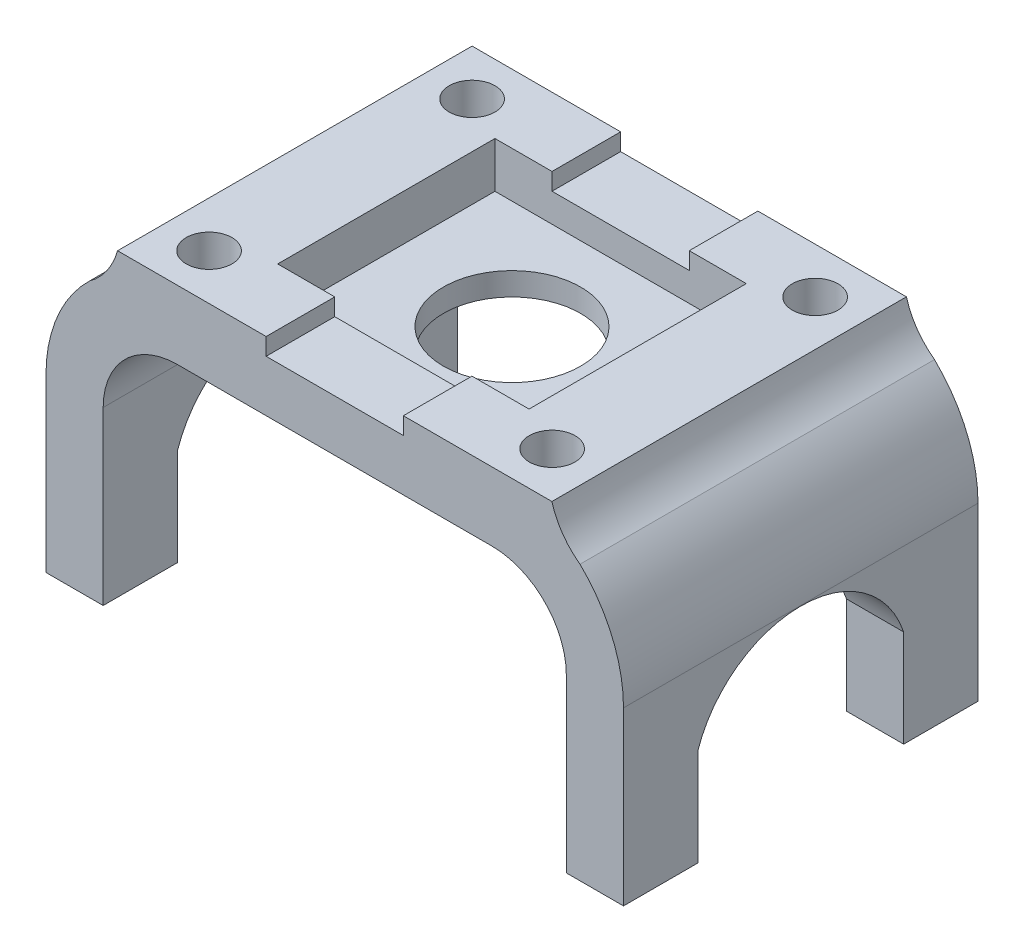
SolidWorks part; units mm, degrees
ref_plane "Piano frontale" through (0, 0, 0) normal (0, 0, 1) x (1, 0, 0)
ref_plane "Piano superiore" through (0, 0, 0) normal (0, 1, 0) x (1, 0, 0)
ref_plane "Piano destro" through (0, 0, 0) normal (1, 0, 0) x (0, 0, -1)
sketch "Schizzo1" plane through (0, 0, 0) normal (0, 0, 1) x (1, 0, 0)
  line L1 (0, 0) -> (-101, 0)
  line L2 (0, 0) -> (0, 55)
  line L3 (0, 55) -> (-101, 55)
  line L4 (-101, 0) -> (-101, 55)
  dimension "D1" = 101
  dimension "D2" = 55
extrude "Estrusione-Estrusione1" add sketch "Schizzo1" against normal blind 62
sketch "Schizzo2" plane through (0, 0, 0) normal (1, 0, 0) x (0, 0, -1)
  line L0 (62, 0) -> (0, 0) construction
  line L1 (13, 0) -> (49, 0)
  line L2 (13, 0) -> (13, 17)
  line L4 (49, 0) -> (49, 17)
  line L5 (0, 0) -> (0, 55) construction
  arc A0 (13, 17) -> (49, 17) centre (31, 10.9172) cw
  dimension "D3" = 19
  dimension "D1" = 13
  dimension "D2" = 36
  dimension "D4" = 17
extrude "Taglio-Estrusione1" cut sketch "Schizzo2" against normal through all
sketch "Schizzo3" plane through (0, 0, 0) normal (0, 0, 1) x (1, 0, 0)
  line L0 (-101, 0) -> (0, 0) construction
  line L1 (-91, 0) -> (-10, 0)
  line L2 (-91, 0) -> (-91, 43) construction
  line L3 (-91, 43) -> (-10, 43) construction
  line L4 (-10, 0) -> (-10, 43) construction
  line L5 (-101, 55) -> (-101, 0) construction
  line L6 (-91, 30) -> (-10, 30) construction
  line L7 (-78, 25.4552) -> (-78, 34.5448) construction
  line L8 (-23, 25.4552) -> (-23, 34.5448) construction
  line L9 (-91, 30) -> (-91, 0)
  line L10 (-78, 43) -> (-23, 43)
  line L11 (-10, 30) -> (-10, 0)
  arc A0 (-91, 30) -> (-78, 43) centre (-78, 30) cw
  arc A1 (-23, 43) -> (-10, 30) centre (-23, 30) cw
  point P13 (-78, 30)
  point P16 (-23, 30)
  dimension "D1" = 81
  dimension "D2" = 10
  dimension "D3" = 43
  dimension "D4" = 30
  dimension "D5" = 13
  dimension "D6" = 13
extrude "Taglio-Estrusione2" cut sketch "Schizzo3" against normal through all
sketch "Schizzo6" plane through (0, 0, 0) normal (0, 0, 1) x (1, 0, 0)
  line L0 (0, 0) -> (0, 55) construction
  line L1 (-10, 0) -> (0, 0) construction
  line L2 (0, 55) -> (-101, 55) construction
  line L3 (0, 55) -> (-12.5, 55) construction
  line L4 (-101, 55) -> (-101, 0) construction
  line L5 (-50.5, 55) -> (-50.5, -49945) construction
  circle A0 centre (-25, 30) radius 25 construction
  circle A1 centre (0, 58.5) radius 13 construction
  point P17 (-50.5, 55)
  dimension "D1" = 25
  dimension "D3" = 101
  dimension "D6" = 50
  dimension "D7" = 26
  dimension "D2" = 30
  dimension "D4" = 3.5
  dimension "D5" = 12.5
sketch "Schizzo7" plane through (0, 0, 0) normal (0, 0, 1) x (1, 0, 0)
  line L0 (0, 55) -> (-101, 55) construction
  line L1 (0, 55) -> (0, 30)
  line L2 (0, 0) -> (0, 55) construction
  line L3 (0, 55) -> (-12.52, 55)
  line L4 (-50.5, 43) -> (-50.5, -49957) construction
  line L5 (-23, 43) -> (-78, 43) construction
  line L7 (-101, 55) -> (-101, 30)
  line L8 (-101, 55) -> (-88.48, 55)
  arc A0 (0, 30) -> (-7.6077, 47.9585) centre (-25, 30) ccw
  circle A1 centre (0, 58.5) radius 13 construction
  arc A2 (-7.6077, 47.9585) -> (-12.52, 55) centre (0, 58.5) cw
  arc A3 (-101, 30) -> (-93.3923, 47.9585) centre (-76, 30) cw
  arc A4 (-93.3923, 47.9585) -> (-88.48, 55) centre (-101, 58.5) ccw
  point P20 (-50.5, 43)
  dimension "D1" = 25
extrude "Taglio-Estrusione4" cut sketch "Schizzo7" against normal through all
sketch "Schizzo8" plane through (0, 55, 0) normal (0, 1, 0) x (1, 0, 0)
  line L0 (-50.5, 62) -> (-50.5, -49938) construction
  line L1 (-12.52, 62) -> (-88.48, 62) construction
  line L2 (-50, 0) -> (0, 0) construction
  line L3 (-62.5, 62) -> (-38.5, 62)
  line L5 (-62.5, 0) -> (-38.5, 0)
  line L6 (-38.5, 62) -> (-38.5, 0)
  line L7 (-62.5, 62) -> (-62.5, 0)
  point P4 (-50.5, 62)
  point P12 (-50.5, 0)
  point P13 (-50.5, 62)
  dimension "D1" = 12
extrude "Taglio-Estrusione5" cut sketch "Schizzo8" against normal blind 3
sketch "Schizzo9" plane through (0, 55, 0) normal (0, 1, 0) x (1, 0, 0)
  line L0 (-12.52, 62) -> (-38.5, 62) construction
  line L1 (-72.48, 50) -> (-28.52, 50)
  line L2 (-72.48, 50) -> (-72.48, 12)
  line L3 (-72.48, 12) -> (-28.52, 12)
  line L4 (-28.52, 50) -> (-28.52, 12)
  line L5 (-50, 0) -> (0, 0) construction
  line L6 (-12.52, 62) -> (-12.52, 0) construction
  line L7 (-88.48, 62) -> (-88.48, 0) construction
  dimension "D1" = 12
  dimension "D2" = 12
  dimension "D3" = 16
  dimension "D4" = 16
extrude "Taglio-Estrusione6" cut sketch "Schizzo9" against normal blind 8
sketch "Schizzo10" plane through (0, 47, 0) normal (0, 1, 0) x (1, 0, 0)
  line L0 (-28.52, 50) -> (-72.48, 12) construction
  circle A0 centre (-50.5, 31) radius 12
  dimension "D1" = 24
extrude "Taglio-Estrusione7" cut sketch "Schizzo10" against normal through all
sketch "Schizzo11" plane through (0, 55, 0) normal (0, 1, 0) x (1, 0, 0)
  line L0 (-88.48, 62) -> (-88.48, 0) construction
  line L1 (-62.5, 62) -> (-88.48, 62) construction
  line L3 (-80.48, 54) -> (-20.48, 54) construction
  line L4 (-80.48, 54) -> (-80.48, 8) construction
  line L5 (-80.48, 8) -> (-20.48, 8) construction
  line L6 (-20.48, 54) -> (-20.48, 8) construction
  circle A0 centre (-80.48, 54) radius 4
  circle A1 centre (-20.48, 54) radius 4
  circle A2 centre (-20.48, 8) radius 4
  circle A3 centre (-80.48, 8) radius 4
  dimension "D3" = 8
  dimension "D1" = 8
  dimension "D2" = 8
  dimension "D4" = 60
  dimension "D5" = 46
extrude "Taglio-Estrusione8" cut sketch "Schizzo11" against normal through all
